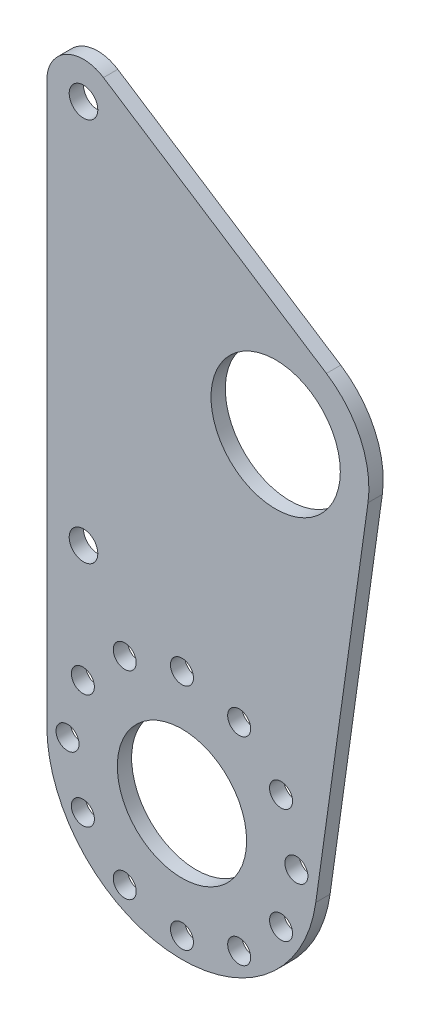
SolidWorks part; units mm, degrees
material "Polypropylene"
ref_plane "Front Plane" through (0, 0, 0) normal (0, 0, 1) x (1, 0, 0)
ref_plane "Top Plane" through (0, 0, 0) normal (0, 1, 0) x (1, 0, 0)
ref_plane "Right Plane" through (0, 0, 0) normal (1, 0, 0) x (0, 0, -1)
sketch "Sketch2" plane through (0, 0, 0) normal (0, 0, 1) x (1, 0, 0)
  line L0 (-139.7, 0) -> (139.7, 0) construction
  line L1 (-139.7, 162.1582) -> (139.7, 162.1582) construction
  line L2 (-139.7, 0) -> (-139.7, 162.1582) construction
  line L3 (89.6578, 156.3951) -> (-88.9, 111.3582) construction
  line L4 (-88.9, 111.3582) -> (87.5277, 58.5898) construction
  line L6 (85.725, 52.9003) -> (82.55, 52.9003) construction
  line L7 (139.7, 162.1582) -> (139.7, 0) construction
  line L8 (-109.7, 30) -> (-102.2692, 59.0652) construction
  line L9 (-102.2692, 59.0652) -> (-101.4828, 62.1412) construction
  line L10 (-101.4828, 62.1412) -> (-88.9, 111.3582) construction
  line L11 (-88.9, 111.3582) -> (85.725, 52.9003) construction
  line L12 (82.55, 52.9003) -> (82.55, 64.2654) construction
  line L13 (-88.9, 111.3582) -> (92.3374, 143.981) construction
  line L14 (82.55, 52.9003) -> (85.725, 0) construction
  line L15 (85.725, 52.9003) -> (92.4089, 52.9003) construction
  line L16 (-131.5562, 154.0144) -> (-88.9, 111.3582) construction
  line L17 (-88.9, 111.3582) -> (88.9, 111.3582) construction
  line L18 (-88.9, 111.3582) -> (88.1045, 162.1582) construction
  line L22 (82.8416, 162.1582) -> (82.8416, 157.3763) construction
  line L23 (82.8416, 157.3763) -> (-88.9, 111.3582) construction
  line L24 (122.2, 107.7485) -> (115.1001, 135.493) construction
  line L25 (-88.9, 111.3582) -> (-131.5562, 68.702) construction
  line L26 (120.5994, 135.493) -> (117.8497, 140.2555) construction
  line L27 (117.8497, 140.2555) -> (112.3505, 140.2555) construction
  line L28 (112.3505, 140.2555) -> (109.6008, 135.493) construction
  line L29 (109.6008, 135.493) -> (112.3505, 130.7305) construction
  line L30 (112.3505, 130.7305) -> (117.8497, 130.7305) construction
  line L31 (117.8497, 130.7305) -> (120.5994, 135.493) construction
  line L40 (-139.7, 154.0144) -> (-139.7, 30)
  line L41 (-131.5562, 161.3468) -> (-137.9062, 157.6806) construction
  line L42 (-137.9062, 157.6806) -> (-137.9062, 150.3483) construction
  line L43 (-137.9062, 150.3483) -> (-131.5562, 146.6821) construction
  line L44 (-131.5562, 146.6821) -> (-125.2062, 150.3483) construction
  line L45 (-125.2062, 150.3483) -> (-125.2062, 157.6806) construction
  line L46 (-125.2062, 157.6806) -> (-131.5562, 161.3468) construction
  line L47 (-131.5562, 61.3697) -> (-125.2062, 65.0358) construction
  line L48 (-125.2062, 65.0358) -> (-125.2062, 72.3682) construction
  line L49 (-125.2062, 72.3682) -> (-131.5562, 76.0344) construction
  line L50 (-131.5562, 76.0344) -> (-137.9062, 72.3682) construction
  line L51 (-137.9062, 72.3682) -> (-137.9062, 65.0358) construction
  line L52 (-137.9062, 65.0358) -> (-131.5562, 61.3697) construction
  line L53 (-79.9907, 25.8335) -> (-68.3996, 108.4832)
  line L54 (-77.6298, 128.7224) -> (-127.1225, 160.8455)
  circle A0 centre (-88.9, 111.3582) radius 50.8 construction
  circle A1 centre (-88.9, 111.3582) radius 14.351
  arc A15 (81.4439, 60.4094) -> (81.4884, 162.1582) centre (-88.9, 111.3582) ccw construction
  arc A16 (92.4089, 52.9003) -> (94.7018, 162.1582) centre (-88.9, 111.3582) ccw construction
  arc A17 (89.6578, 156.3951) -> (87.5277, 58.5898) centre (-88.9, 111.3582) cw construction
  arc A18 (90.2045, 57.7892) -> (92.367, 157.0784) centre (-88.9, 111.3582) ccw construction
  arc A19 (84.8508, 59.3905) -> (86.9487, 155.7118) centre (-88.9, 111.3582) ccw construction
  arc A20 (84.8508, 59.3905) -> (90.2045, 57.7892) centre (87.5277, 58.5898) ccw construction
  arc A21 (92.367, 157.0784) -> (86.9487, 155.7118) centre (89.6578, 156.3951) ccw construction
  arc A23 (89.6578, 156.3951) -> (88.1045, 162.1582) centre (-88.9, 111.3582) ccw construction
  circle A24 centre (107.0837, 151.3632) radius 9.525 construction
  circle A25 centre (122.2, 107.7485) radius 17.5 construction
  circle A26 centre (122.2, 107.7485) radius 4.826 construction
  circle A27 centre (115.1001, 135.493) radius 23.8125 construction
  circle A28 centre (107.0837, 151.3632) radius 10.795 construction
  circle A29 centre (-109.7, 30) radius 30 construction
  circle A30 centre (-109.7, 30) radius 25.4 construction
  circle A31 centre (-109.7, 55.4) radius 2.5527
  circle A32 centre (-97, 51.997) radius 2.5527
  circle A33 centre (-87.703, 42.7) radius 2.5527
  circle A34 centre (-84.3, 30) radius 2.5527
  circle A35 centre (-87.703, 17.3) radius 2.5527
  circle A36 centre (-97, 8.003) radius 2.5527
  circle A37 centre (-109.7, 4.6) radius 2.5527
  circle A38 centre (-122.4, 8.003) radius 2.5527
  circle A39 centre (-131.697, 17.3) radius 2.5527
  circle A40 centre (-135.1, 30) radius 2.5527
  circle A41 centre (-131.697, 42.7) radius 2.5527
  circle A42 centre (-122.4, 51.997) radius 2.5527
  arc A43 (87.5277, 58.5898) -> (85.725, 52.9003) centre (-88.9, 111.3582) cw construction
  circle A44 centre (-109.7, 30) radius 14.351
  circle A48 centre (115.1001, 135.493) radius 24.5999 construction
  circle A49 centre (122.2, 107.7485) radius 12.5 construction
  circle A50 centre (134.3098, 110.8474) radius 1.25 construction
  circle A51 centre (125.2989, 95.6387) radius 1.25 construction
  circle A52 centre (110.0902, 104.6496) radius 1.25 construction
  circle A53 centre (119.1011, 119.8583) radius 1.25 construction
  circle A54 centre (115.1001, 135.493) radius 4.7625 construction
  circle A55 centre (115.1001, 135.493) radius 8.89 construction
  circle A56 centre (115.1001, 135.493) radius 10.16 construction
  circle A59 centre (107.0837, 151.3632) radius 8.89 construction
  circle A60 centre (107.0837, 151.3632) radius 10.16 construction
  circle A61 centre (89.6578, 156.3951) radius 2.5527 construction
  circle A62 centre (92.3374, 143.981) radius 2.5527 construction
  circle A63 centre (-131.5562, 68.702) radius 3.175
  circle A64 centre (-131.5562, 154.0144) radius 3.175
  circle A65 centre (-131.5562, 154.0144) radius 6.35 construction
  circle A66 centre (-131.5562, 68.702) radius 6.35 construction
  arc A67 (-139.7, 30) -> (-79.9907, 25.8335) centre (-109.7, 30) ccw
  arc A69 (-127.1225, 160.8455) -> (-139.7, 154.0144) centre (-131.5562, 154.0144) ccw
  arc A70 (-68.3996, 108.4832) -> (-77.6298, 128.7224) centre (-88.9, 111.3582) ccw
  point P6 (-88.9, 60.5582)
  point P10 (-109.7, 0)
  point P11 (86.727, 55.913)
  point P30 (-88.9, 111.3582)
  point P32 (0, 0)
  point P36 (0, 162.1582)
  point P37 (-88.9, 162.1582)
  point P42 (95.2063, 107.3484)
  point P66 (-109.7, 30)
  point P68 (-139.7, 30)
  point P82 (88.954, 159.099)
  point P85 (-79.7, 30)
  point P92 (88.1045, 162.1582)
  point P105 (122.2, 107.7485)
  dimension "D1" = 101.6
  dimension "D2" = 28.702
  dimension "D3" = 60
  dimension "D4" = 50.8
  dimension "D9" = 127
  dimension "D10" = 12.7
  dimension "D11" = 6.35
  dimension "D12" = 2.794
  dimension "D16" = 35
  dimension "D17" = 9.652
  dimension "D18" = 47.625
  dimension "D19" = 19.05
  dimension "D20" = 17.78
  dimension "D5" = 5.1054
  dimension "D13" = 85.725
  dimension "D25" = 28.702
  dimension "D21" = 82.55
  dimension "D22" = 186.944
  dimension "D30" = 49.1998
  dimension "D31" = 60.325
  dimension "D32" = 26.856
  dimension "D33" = 12.7
  dimension "D34" = 25
  dimension "D35" = 2.5
  dimension "D37" = 9.525
  dimension "D38" = 17.78
  dimension "D39" = 20.32
  dimension "D40" = 6.35
  dimension "D42" = 20.32
  dimension "D43" = 21.59
  dimension "D28" = 5.1054
  dimension "D29" = 6.35
  dimension "D6" = 12
  dimension "D7" = 15
  dimension "D8" = 279.4
  dimension "D14" = 3.175
  dimension "D15" = 279.4
  dimension "D23" = 3.175
  dimension "D24" = 3.175
  dimension "D26" = 3.175
  dimension "D27" = 12.7
  dimension "D36" = 4
extrude "Boss-Extrude1" add sketch "Sketch2" along normal blind 3.175
